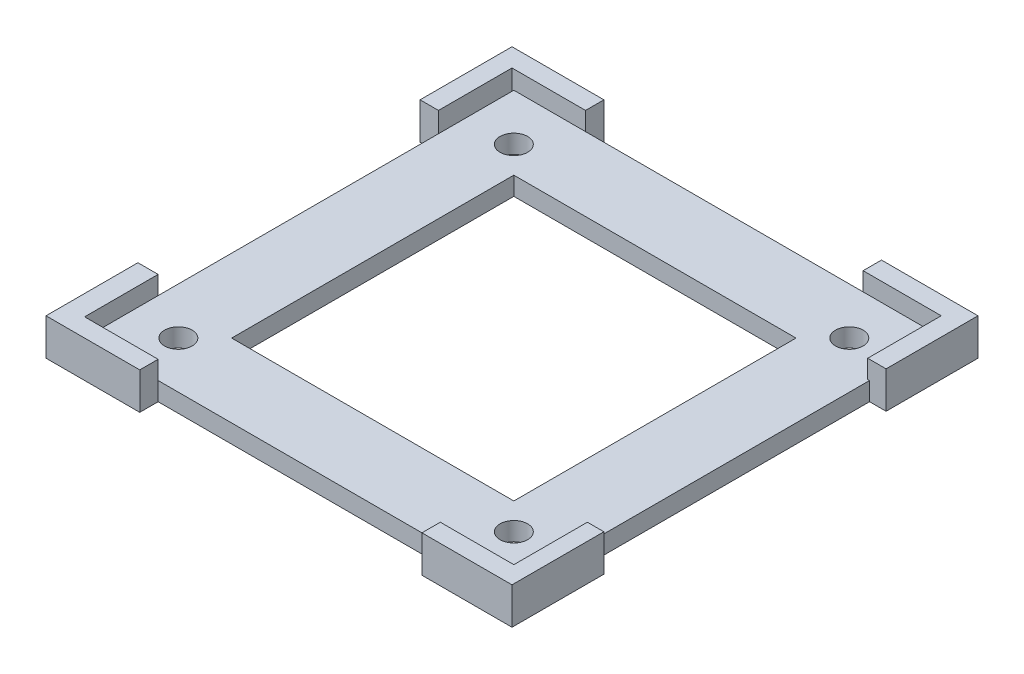
SolidWorks part; units mm, degrees
ref_plane "Front Plane" through (0, 0, 0) normal (0, 0, 1) x (1, 0, 0)
ref_plane "Top Plane" through (0, 0, 0) normal (0, 1, 0) x (1, 0, 0)
ref_plane "Right Plane" through (0, 0, 0) normal (1, 0, 0) x (0, 0, -1)
sketch "Sketch1" plane through (0, 0, 0) normal (0, 1, 0) x (1, 0, 0)
  line L4 (-22.0056, -21.8146) -> (-14.0056, -21.8146)
  line L5 (-22.0056, -21.8146) -> (-22.0056, -15.3146)
  line L8 (24.6944, -21.8146) -> (16.6944, -21.8146)
  line L9 (24.6944, -21.8146) -> (24.6944, -13.8146)
  line L13 (24.6944, 24.8854) -> (24.6944, 16.6691)
  line L16 (-22.0056, 15.3854) -> (-22.0056, -15.3146)
  line L17 (-14.0056, 16.8854) -> (-14.0056, -13.8146)
  line L18 (-14.0056, -13.8146) -> (16.6944, -13.8146)
  line L19 (16.6944, -13.8146) -> (16.6944, 16.8854)
  line L20 (16.6944, 16.8854) -> (-14.0056, 16.8854)
  line L22 (24.6944, 16.6691) -> (24.6944, -13.8146)
  line L23 (16.6944, -21.8146) -> (-14.0056, -21.8146)
  line L24 (15.5799, 21.2854) -> (23.4307, 21.2854) construction
  line L25 (21.0944, 19.7854) -> (21.0944, 15.3454) construction
  line L26 (24.6944, 24.8854) -> (-22.0056, 24.8854)
  line L27 (-22.0056, 24.8854) -> (-22.0056, 15.3854)
  line L28 (19.5944, -18.2146) -> (15.1442, -18.2146) construction
  line L29 (19.5944, 19.7854) -> (-16.9056, 19.7854) construction
  line L30 (-18.4056, -16.7146) -> (-18.4056, -21.8146) construction
  line L31 (-16.9056, -18.2146) -> (-13.8352, -18.2146) construction
  line L32 (-18.4056, 19.7854) -> (-18.4056, 22.6381) construction
  line L33 (-16.9056, 21.2854) -> (-13.6352, 21.2854) construction
  line L34 (21.0944, -16.7146) -> (21.0944, -20.0317) construction
  circle A0 centre (-16.9056, 19.7854) radius 1.5
  circle A1 centre (-16.9056, -16.7146) radius 1.5
  circle A2 centre (19.5944, 19.7854) radius 1.5
  circle A3 centre (19.5944, -16.7146) radius 1.5
  dimension "D9" = 3
  dimension "D4" = 3.6
  dimension "D6" = 8
  dimension "D2" = 8
  dimension "D3" = 46.7
  dimension "D5" = 3.6
  dimension "D7" = 8
  dimension "D8" = 8
  dimension "D10" = 3.6
  dimension "D12" = 46.7
  dimension "D13" = 3.6
extrude "Boss-Extrude1" add sketch "Sketch1" along normal blind 2
sketch "Sketch3" plane through (0, 0, 0) normal (0, 1, 0) x (1, 0, 0)
  line L0 (-14.2056, 24.8854) -> (-14.2056, 26.8854)
  line L1 (-14.2056, 26.8854) -> (-24.2056, 26.8854)
  line L2 (-24.2056, 26.8854) -> (-24.2056, 16.8854)
  line L3 (-24.2056, 16.8854) -> (-22.2056, 16.8854)
  line L4 (-22.0056, 24.8854) -> (-22.0056, -21.8146) construction
  line L5 (-22.2056, 16.8854) -> (-22.2056, 24.8854)
  line L6 (-22.2056, 24.8854) -> (-14.2056, 24.8854)
  line L7 (-22.0056, -13.8146) -> (-24.2056, -13.8146)
  line L8 (-24.2056, -13.8146) -> (-24.2056, -23.8146)
  line L9 (-24.2056, -23.8146) -> (-14.0056, -23.8146)
  line L10 (-14.0056, -23.8146) -> (-14.0056, -21.8146)
  line L11 (-22.0056, -21.8146) -> (24.6944, -21.8146) construction
  line L12 (-14.0056, -21.8146) -> (-22.0056, -21.8146)
  line L13 (-22.0056, -21.8146) -> (-22.0056, -13.8146)
  line L14 (15.9944, 26.8854) -> (26.4944, 26.8854)
  line L15 (26.4944, 26.8854) -> (26.4944, 16.8854)
  line L16 (26.4944, 16.8854) -> (24.4944, 16.8854)
  line L17 (24.4944, 16.8854) -> (24.4944, 24.8854)
  line L20 (24.4944, 24.8854) -> (15.9944, 24.8854)
  line L21 (15.9944, 24.8854) -> (15.9944, 26.8854)
  line L22 (16.6944, -21.8146) -> (16.6944, -23.8146)
  line L23 (16.6944, -23.8146) -> (26.4944, -23.8146)
  line L24 (26.4944, -23.8146) -> (26.4944, -13.8146)
  line L25 (26.4944, -13.8146) -> (24.6944, -13.8146)
  line L26 (24.6944, -21.8146) -> (24.6944, 24.8854) construction
  line L27 (24.6944, -13.8146) -> (24.6944, -21.8146)
  line L28 (24.6944, -21.8146) -> (16.6944, -21.8146)
  line L29 (-14.0056, -13.8146) -> (16.6944, -13.8146) construction
  line L30 (24.6944, 24.8854) -> (-22.0056, 24.8854) construction
  line L31 (16.6944, 16.8854) -> (-14.0056, 16.8854) construction
  dimension "D1" = 2
  dimension "D2" = 2
  dimension "D3" = 2
  dimension "D4" = 2
extrude "Boss-Extrude2" add sketch "Sketch3" along normal blind 4
